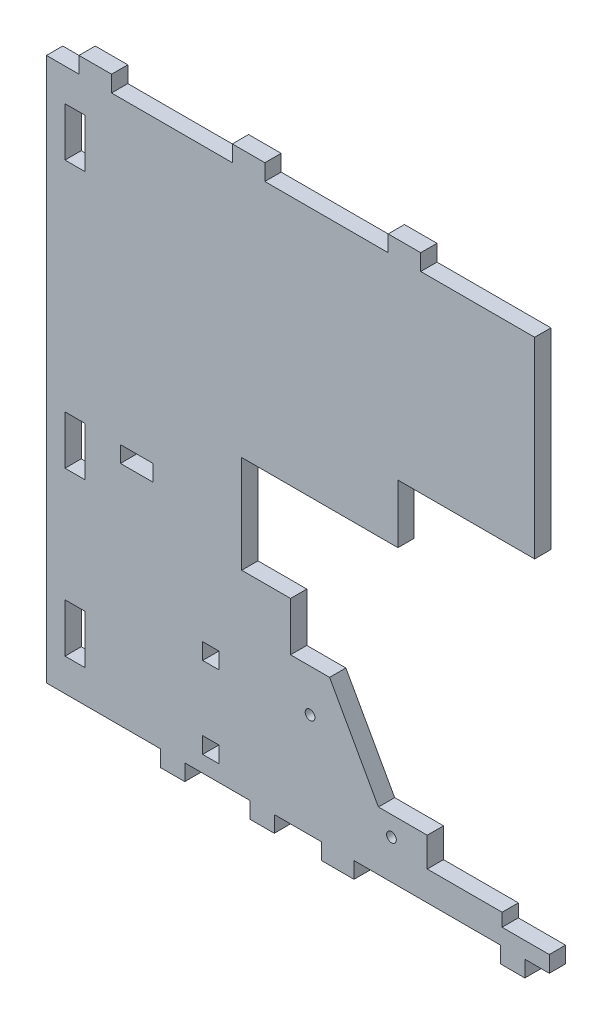
SolidWorks part; units mm, degrees
ref_plane "Plan de face" through (0, 0, 0) normal (0, 0, 1) x (1, 0, 0)
ref_plane "Plan de dessus" through (0, 0, 0) normal (0, 1, 0) x (1, 0, 0)
ref_plane "Plan de droite" through (0, 0, 0) normal (1, 0, 0) x (0, 0, -1)
sketch "Esquisse1" plane through (0, 0, 0) normal (0, 0, 1) x (1, 0, 0)
  line L1 (0, 0) -> (37, 0)
  line L2 (0, 0) -> (0, 45)
  line L3 (0, 45) -> (12, 45)
  line L4 (37, 0) -> (37, 18)
  line L6 (12, 45) -> (27, 18)
  line L7 (27, 18) -> (37, 18)
  circle A0 centre (6, 32) radius 1.5
  circle A1 centre (31, 12) radius 1.5
  dimension "D3" = 20
  dimension "D4" = 3
  dimension "D1" = 6
  dimension "D2" = 45
  dimension "D5" = 12
  dimension "D6" = 12
  dimension "D7" = 25
  dimension "D8" = 6
  dimension "D9" = 6
  dimension "D10" = 10
extrude "Boss.-Extru.1" add sketch "Esquisse1" along normal blind 5
sketch "Esquisse2" plane through (0, 0, 5) normal (0, 0, 1) x (1, 0, 0)
  line L0 (37, 18) -> (27, 18) construction
  line L2 (37, 0) -> (37, 18)
  line L3 (37, 0) -> (64.5, 0)
  line L4 (12, 45) -> (0, 45) construction
  line L5 (72, 0) -> (72, -5)
  line L6 (72, -5) -> (64.5, -5)
  line L7 (64.5, 0) -> (64.5, -5)
  line L8 (72, 0) -> (79.5, 0)
  line L12 (0, 0) -> (-5, 0)
  line L13 (0, 0) -> (0, 60)
  line L14 (0, 60) -> (-15, 60)
  line L15 (40, 167) -> (75, 167)
  line L16 (-12.5, 0) -> (-32.5, 0)
  line L17 (-40, 0) -> (-40, -5)
  line L18 (-15, 60) -> (-15, 90)
  line L19 (-40, -5) -> (-32.5, -5)
  line L20 (-75, 0) -> (-75, 167)
  line L21 (-75, 167) -> (-65, 167)
  line L22 (-32.5, 0) -> (-32.5, -5)
  line L23 (33, 90) -> (-15, 90)
  line L24 (75, 167) -> (75, 108)
  line L25 (-12.5, 0) -> (-12.5, -5)
  line L26 (-12.5, -5) -> (-5, -5)
  line L27 (-5, 0) -> (-5, -5)
  line L28 (-40, 0) -> (-75, 0)
  line L29 (-65, 167) -> (-65, 172)
  line L30 (-65, 172) -> (-55, 172)
  line L31 (-55, 167) -> (-55, 172)
  line L32 (-55, 167) -> (30, 167)
  line L33 (40, 167) -> (40, 172)
  line L34 (40, 172) -> (30, 172)
  line L35 (30, 167) -> (30, 172)
  line L36 (-69.2981, 10) -> (-63.1592, 10)
  line L37 (-69.2981, 10) -> (-69.2981, 25)
  line L38 (33, 90) -> (33, 108)
  line L39 (33, 108) -> (75, 108)
  line L40 (-63.1592, 10) -> (-63.1592, 25)
  line L41 (-69.2981, 25) -> (-63.1592, 25)
  line L42 (-69.2981, 10) -> (-69.2981, 0) construction
  line L43 (-63.1592, 25) -> (-63.1592, 10) construction
  line L45 (-69.2981, 75) -> (-63.1592, 75)
  line L46 (-69.2981, 75) -> (-69.2981, 60)
  line L47 (-69.2981, 60) -> (-63.1592, 60)
  line L48 (-63.1592, 75) -> (-63.1592, 60)
  line L49 (-69.2981, 142) -> (-63.1592, 142)
  line L50 (-69.2981, 142) -> (-69.2981, 157)
  line L51 (-69.2981, 157) -> (-63.1592, 157)
  line L52 (-63.1592, 142) -> (-63.1592, 157)
  line L53 (-22, 5) -> (-27, 5)
  line L54 (-22, 5) -> (-22, 10)
  line L55 (-22, 10) -> (-27, 10)
  line L56 (-27, 5) -> (-27, 10)
  line L57 (-27, 35) -> (-22, 35)
  line L58 (-27, 35) -> (-27, 30)
  line L59 (-27, 30) -> (-22, 30)
  line L60 (-22, 35) -> (-22, 30)
  line L62 (37, 18) -> (42, 18)
  line L63 (37, 18) -> (37, 8.9214)
  line L64 (65, 9) -> (65, 5)
  line L65 (42, 18) -> (42, 9)
  line L66 (65, 5) -> (79.5, 5)
  line L67 (79.5, 0) -> (79.5, 5)
  line L68 (65, 9) -> (42, 9)
  circle A0 centre (31, 12) radius 1.5 construction
  dimension "D24" = 11
  dimension "D25" = 3
  dimension "D1" = 42.5
  dimension "D3" = 27.5
  dimension "D4" = 4
  dimension "D5" = 5
  dimension "D6" = 15
  dimension "D7" = 15
  dimension "D8" = 167
  dimension "D9" = 18
  dimension "D10" = 5
  dimension "D11" = 20
  dimension "D12" = 75
  dimension "D13" = 75
  dimension "D14" = 5
  dimension "D15" = 10
  dimension "D16" = 85
  dimension "D17" = 10
  dimension "D18" = 48
  dimension "D19" = 10
  dimension "D20" = 15
  dimension "D21" = 35
  dimension "D22" = 10
  dimension "D23" = 30
  dimension "D26" = 5
  dimension "D27" = 23
  dimension "D28" = 7.5
extrude "Boss.-Extru.2" add sketch "Esquisse2" against normal blind 5
sketch "Esquisse3" plane through (0, 0, 0) normal (0, 0, -1) x (-1, 0, 0)
  line L0 (5, 0) -> (-64.5, 0) construction
  line L1 (-19.5, 0) -> (-9.5, 0)
  line L2 (-19.5, 0) -> (-19.5, -5)
  line L3 (-19.5, -5) -> (-9.5, -5)
  line L4 (-9.5, 0) -> (-9.5, -5)
  line L5 (-79.5, 0) -> (-79.5, 5) construction
  line L6 (55, 167) -> (-30, 167) construction
  line L7 (7.8934, 167) -> (17.8934, 167)
  line L8 (7.8934, 167) -> (7.8934, 172)
  line L9 (7.8934, 172) -> (17.8934, 172)
  line L10 (17.8934, 167) -> (17.8934, 172)
  dimension "D1" = 10
  dimension "D2" = 5
  dimension "D3" = 60
  dimension "D4" = 10
  dimension "D5" = 5
extrude "Boss.-Extru.3" add sketch "Esquisse3" against normal blind 5
sketch "Esquisse4" plane through (0, 0, 0) normal (0, 0, -1) x (-1, 0, 0)
  line L0 (42.27, 74.8) -> (42.27, 69.8)
  line L1 (42.27, 74.8) -> (52.272, 74.8)
  line L2 (42.27, 69.8) -> (52.272, 69.8)
  line L3 (52.272, 74.8) -> (52.272, 69.8)
  line L4 (-75, 167) -> (-75, 108) construction
  line L5 (12.5, -5) -> (5, -5) construction
  dimension "D1" = 87.5
  dimension "D2" = 117.27
  dimension "D3" = 127.272
  dimension "D4" = 74.8
  dimension "D5" = 79.8
  dimension "D6" = 172
extrude "Enlèv. mat.-Extru.1" cut sketch "Esquisse4" against normal blind 10
